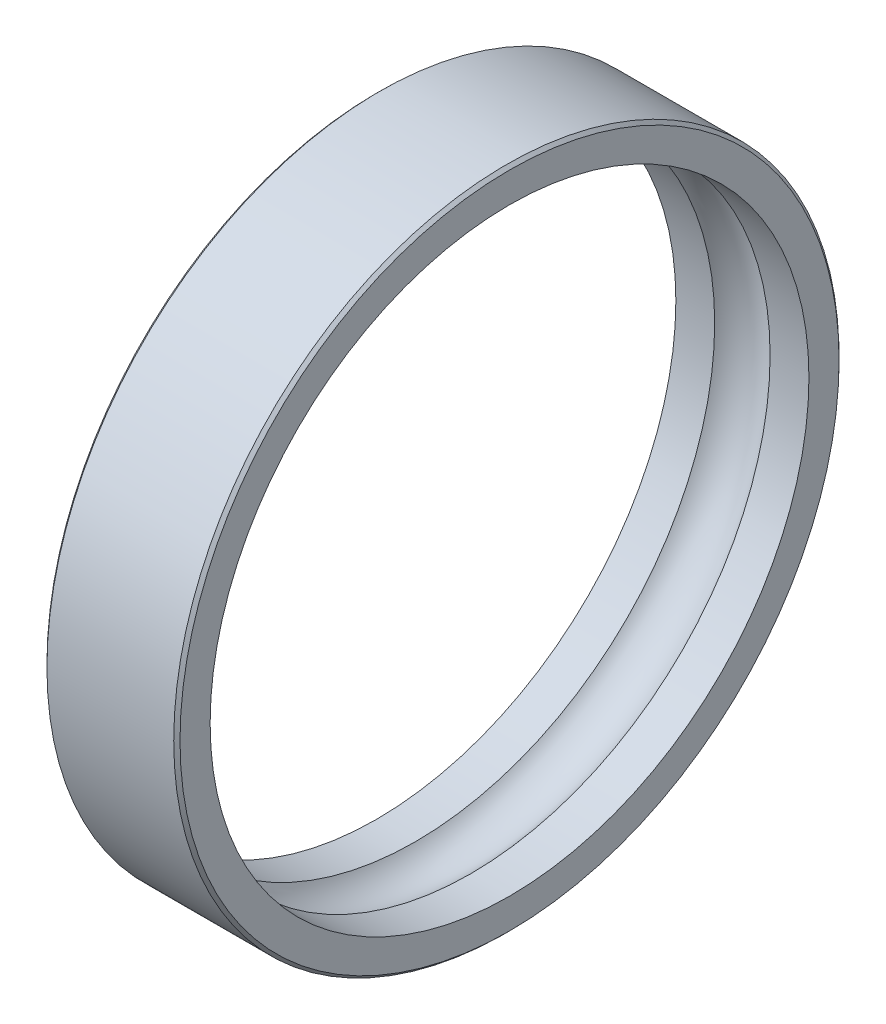
SolidWorks part; units mm, degrees
material "1.2083 (X40Cr14)"
ref_plane "Płaszczyzna przednia" through (0, 0, 0) normal (0, 0, 1) x (1, 0, 0)
ref_plane "Płaszczyzna górna" through (0, 0, 0) normal (0, 1, 0) x (1, 0, 0)
ref_plane "Płaszczyzna prawa" through (0, 0, 0) normal (1, 0, 0) x (0, 0, -1)
sketch "Szkic1" plane through (0, 0, 0) normal (0, 0, 1) x (1, 0, 0)
  line L0 (0, -14.3051) -> (0, 14.3051) construction
  line L1 (-10.262, 0) -> (10.262, 0) construction
  line L2 (-1.4293, 5) -> (1.4293, 5)
  line L3 (1.4293, 5) -> (1.5, 5.0707)
  line L4 (1.5, 5.0707) -> (1.5, 5.75)
  line L5 (1.5, 5.75) -> (0.6245, 5.75)
  line L6 (-1.5, 6.75) -> (-0.6245, 6.75)
  line L7 (1.5, 6.75) -> (1.5, 7.4293)
  line L8 (1.5, 7.4293) -> (1.4293, 7.5)
  line L9 (1.4293, 7.5) -> (-1.4293, 7.5)
  line L10 (-1.4293, 5) -> (-1.5, 5.0707)
  line L11 (-1.5, 5.0707) -> (-1.5, 5.75)
  line L12 (-1.5, 7.4293) -> (-1.4293, 7.5)
  line L13 (-1.5, 6.75) -> (-1.5, 7.4293)
  line L14 (0.6245, 6.75) -> (1.5, 6.75)
  line L15 (-0.6245, 5.75) -> (-1.5, 5.75)
  arc A0 (0.6245, 6.75) -> (-0.6245, 6.75) centre (0, 6.25) ccw
  arc A1 (-0.6245, 5.75) -> (0.6245, 5.75) centre (0, 6.25) ccw
  point P6 (0, 0)
  point P21 (0, 5)
  point P23 (0, 7.05)
  point P26 (0, 7.5)
  dimension "D8" = 1.6
  dimension "D1" = 10
  dimension "D2" = 0.1
  dimension "D3" = 15
  dimension "D4" = 1
  dimension "D5" = 135
  dimension "D6" = 3
  dimension "D7" = 0.5
revolve "Obrót1" add sketch "Szkic1" angle 360 about L1
sketch "Szkic2" plane through (0, 0, 0) normal (1, 0, 0) x (0, 0, -1)
  circle A0 centre (0, 0) radius 7.05 construction
